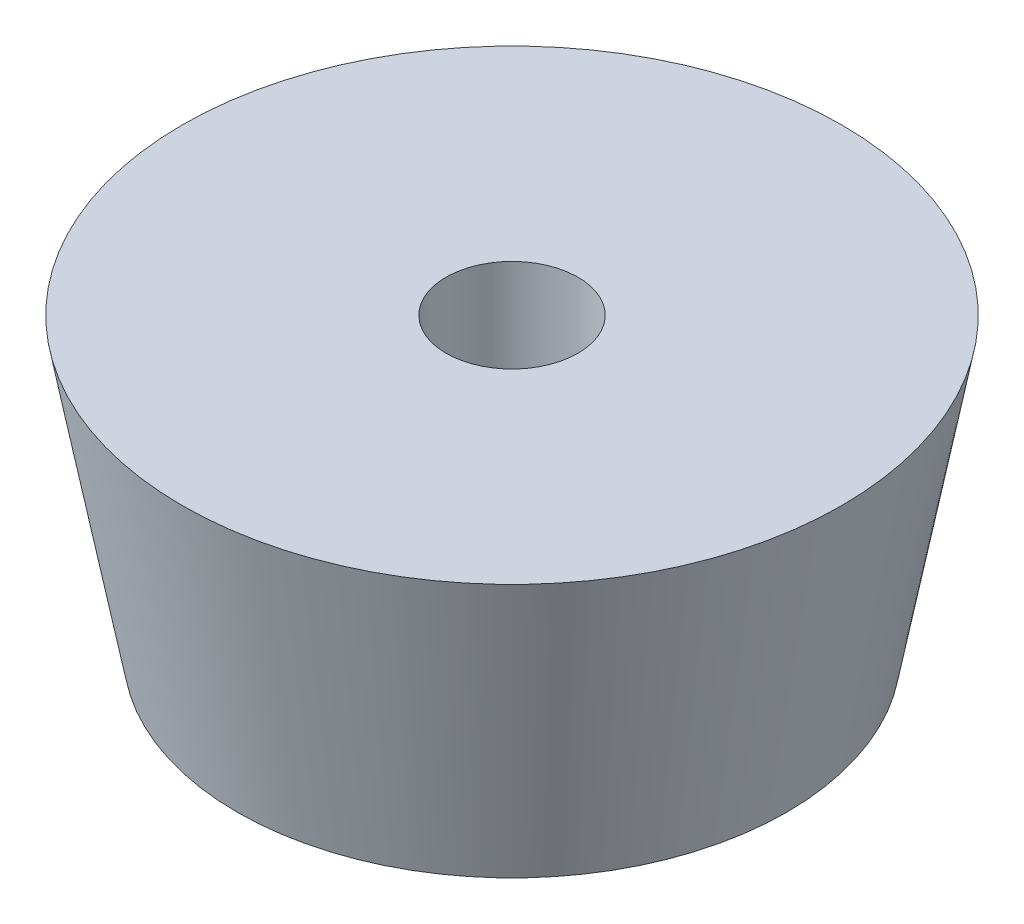
SolidWorks part; units mm, degrees
ref_plane "Front Plane" through (0, 0, 0) normal (0, 0, 1) x (1, 0, 0)
ref_plane "Top Plane" through (0, 0, 0) normal (0, 1, 0) x (1, 0, 0)
ref_plane "Right Plane" through (0, 0, 0) normal (1, 0, 0) x (0, 0, -1)
sketch "Sketch1" plane through (0, 0, 0) normal (0, 0, 1) x (1, 0, 0)
  line L0 (0, 0) -> (0, 8) construction
  line L1 (-4, 0) -> (-4, 4)
  line L2 (-4, 4) -> (-1.8, 4)
  line L3 (-1.8, 4) -> (-1.8, 8)
  line L4 (-1.8, 8) -> (-9, 8)
  line L5 (-9, 8) -> (-7.5, 0)
  line L6 (-7.5, 0) -> (-4, 0)
  dimension "D1" = 3.6
  dimension "D2" = 15
  dimension "D3" = 8
  dimension "D4" = 4
  dimension "D5" = 8
  dimension "D6" = 18
revolve "Revolve1" add sketch "Sketch1" angle 360 about L0
